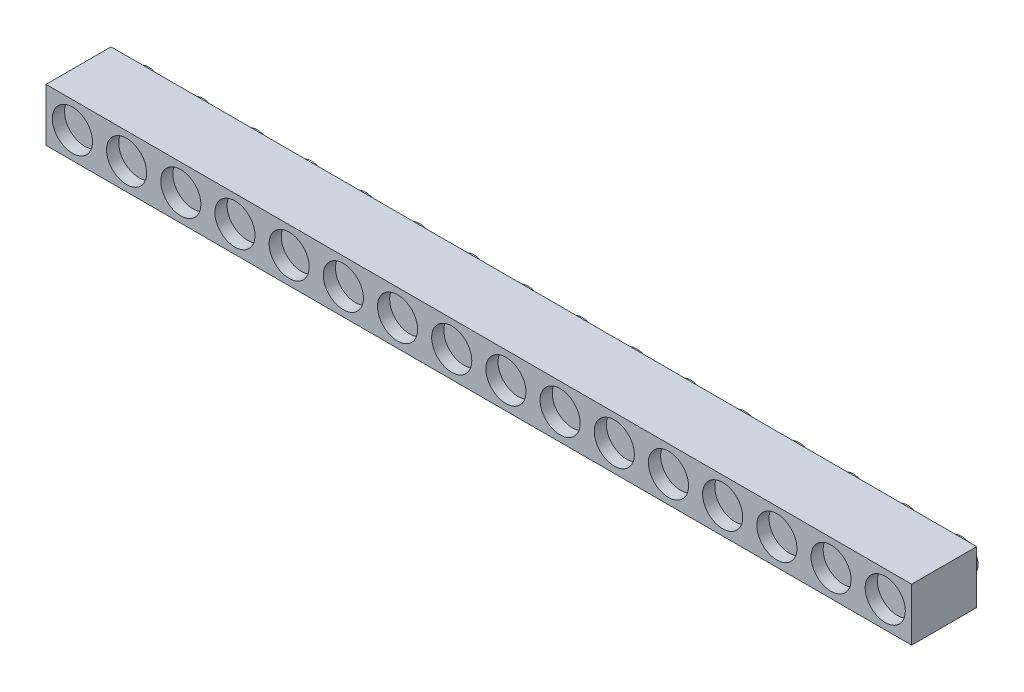
SolidWorks part; units mm, degrees
ref_plane "Спереди" through (0, 0, 0) normal (0, 0, 1) x (1, 0, 0)
ref_plane "Сверху" through (0, 0, 0) normal (0, 1, 0) x (1, 0, 0)
ref_plane "Справа" through (0, 0, 0) normal (1, 0, 0) x (0, 0, -1)
sketch "Эскиз1" plane through (0, 0, 0) normal (0, 0, 1) x (1, 0, 0)
  line L1 (-63.9, -3.9) -> (63.9, -3.9)
  line L2 (-63.9, -3.9) -> (-63.9, 3.9)
  line L3 (-63.9, 3.9) -> (63.9, 3.9)
  line L4 (63.9, -3.9) -> (63.9, 3.9)
  line L5 (-63.9, -3.9) -> (63.9, 3.9) construction
  line L6 (-63.9, 3.9) -> (63.9, -3.9) construction
  point P0 (0, 0)
  dimension "D1" = 127.8
  dimension "D2" = 7.8
extrude "Бобышка-Вытянуть1" add sketch "Эскиз1" along normal blind 9.6
sketch "Эскиз2" plane through (0, 0, 0) normal (0, 0, -1) x (-1, 0, 0)
  line L0 (-63.9, -3.9) -> (-63.9, 3.9) construction
  line L1 (-63.9, 3.9) -> (63.9, 3.9) construction
  circle A0 centre (-60, 0) radius 2.4
  circle A1 centre (-52, 0) radius 2.4
  circle A2 centre (-44, 0) radius 2.4
  circle A3 centre (-36, 0) radius 2.4
  circle A4 centre (-28, 0) radius 2.4
  circle A5 centre (-20, 0) radius 2.4
  circle A6 centre (-12, 0) radius 2.4
  circle A7 centre (-4, 0) radius 2.4
  circle A8 centre (4, 0) radius 2.4
  circle A9 centre (12, 0) radius 2.4
  circle A10 centre (20, 0) radius 2.4
  circle A11 centre (28, 0) radius 2.4
  circle A12 centre (36, 0) radius 2.4
  circle A13 centre (44, 0) radius 2.4
  circle A14 centre (52, 0) radius 2.4
  circle A15 centre (60, 0) radius 2.4
  dimension "D1" = 3.9
  dimension "D2" = 3.9
  dimension "D3" = 16
extrude "Бобышка-Вытянуть2" add sketch "Эскиз2" along normal blind 1.7
sketch "Эскиз3" plane through (0, 0, 9.6) normal (0, 0, 1) x (1, 0, 0)
  line L0 (-63.9, -3.9) -> (63.9, -3.9) construction
  line L1 (63.9, -3.9) -> (63.9, 3.9) construction
  circle A1 centre (60, 0) radius 2.9623
  circle A2 centre (52, 0) radius 2.9623
  circle A3 centre (44, 0) radius 2.9623
  circle A4 centre (36, 0) radius 2.9623
  circle A5 centre (28, 0) radius 2.9623
  circle A6 centre (20, 0) radius 2.9623
  circle A7 centre (12, 0) radius 2.9623
  circle A8 centre (4, 0) radius 2.9623
  circle A9 centre (-4, 0) radius 2.9623
  circle A10 centre (-12, 0) radius 2.9623
  circle A11 centre (-20, 0) radius 2.9623
  circle A12 centre (-28, 0) radius 2.9623
  circle A13 centre (-36, 0) radius 2.9623
  circle A14 centre (-44, 0) radius 2.9623
  circle A15 centre (-52, 0) radius 2.9623
  circle A16 centre (-60, 0) radius 2.9623
  dimension "D1" = 3.9
  dimension "D2" = 3.9
  dimension "D3" = 16
extrude "Вырез-Вытянуть1" cut sketch "Эскиз3" against normal blind 1.8
